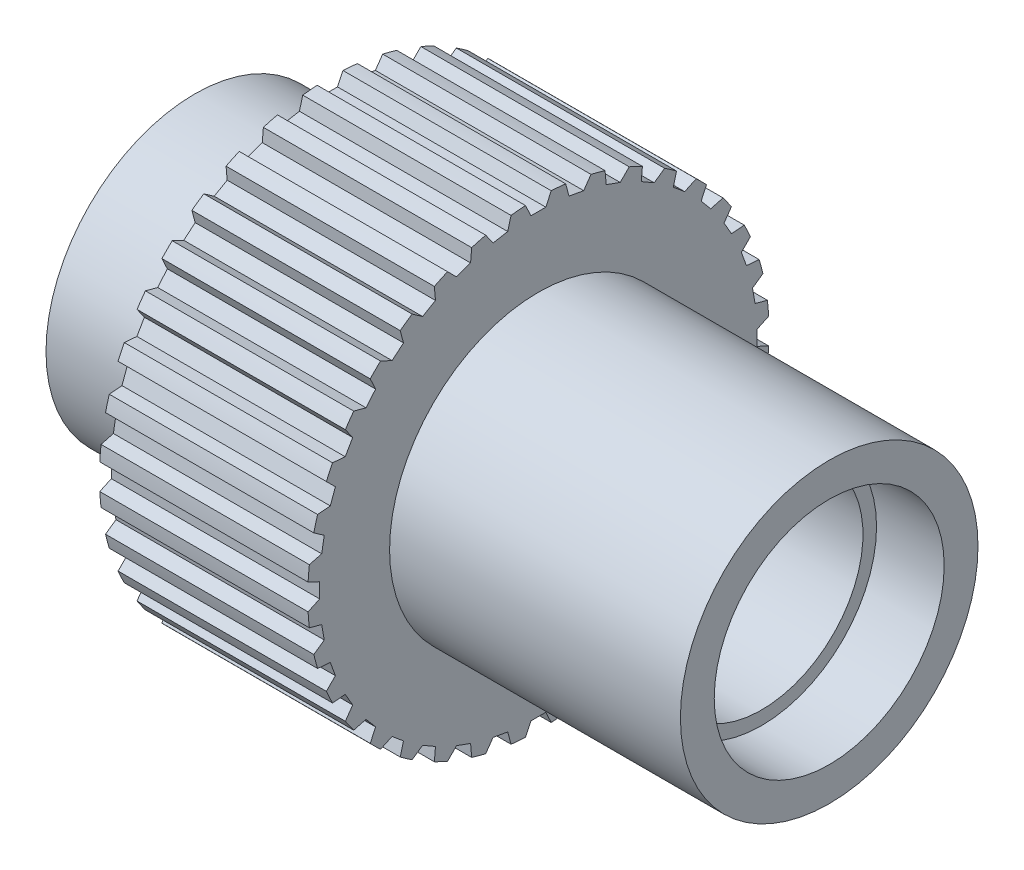
SolidWorks part; units mm, degrees
ref_plane "Plan de face" through (0, 0, 0) normal (0, 0, 1) x (1, 0, 0)
ref_plane "Plan de dessus" through (0, 0, 0) normal (0, 1, 0) x (1, 0, 0)
ref_plane "Plan de droite" through (0, 0, 0) normal (1, 0, 0) x (0, 0, -1)
sketch "Esquisse1" plane through (0, 0, 0) normal (0, 0, 1) x (1, 0, 0)
  line L0 (21.5, 8.5) -> (21.5, 11)
  line L1 (21.5, 11) -> (0, 11)
  line L2 (0, 11) -> (0, 17.05)
  line L3 (0, 17.05) -> (-15.4, 17.05)
  line L4 (-15.4, 17.05) -> (-15.4, 11)
  line L5 (-15.4, 11) -> (-25.4, 11)
  line L6 (-25.4, 11) -> (-25.4, 8.5)
  line L7 (-31.5376, 0) -> (37.2209, 0) construction
  line L8 (21.5, 8.5) -> (16.5, 8.5)
  line L9 (16.5, 8.5) -> (16.5, 7.4979)
  line L10 (16.5, 7.4979) -> (-3.2289, 7.4979)
  line L11 (-3.2289, 7.4979) -> (-3.2289, 8.5)
  line L12 (-3.2289, 8.5) -> (-25.4, 8.5)
  dimension "D1" = 11
  dimension "D2" = 8.5
  dimension "D3" = 17.05
  dimension "D4" = 15.4
  dimension "D5" = 5
  dimension "D6" = 10
  dimension "D7" = 8.5
  dimension "D8" = 21.5
revolve "Révolution1" add sketch "Esquisse1" angle 360 about L7
sketch "Esquisse2" plane through (-15.4, 0, 0) normal (-1, 0, 0) x (0, 0, 1)
  line L0 (-1, 17.1319) -> (-0.5511, 16.1693)
  line L1 (-0.5511, 16.1693) -> (0.5511, 16.1693)
  line L2 (0.5511, 16.1693) -> (1, 17.1319)
  line L3 (1, 17.1319) -> (-1, 17.1319)
  line L4 (0, 0) -> (0, 26.9885) construction
  dimension "D1" = 50
  dimension "D2" = 25
  dimension "D3" = 2
  dimension "D4" = 1
extrude "Extrusion1" cut sketch "Esquisse2" against normal through all
pattern_circular "Répétition circulaire1" count 36 every 10 about axis through (0, 0, 0) along (1, 0, 0) of "Extrusion1"
